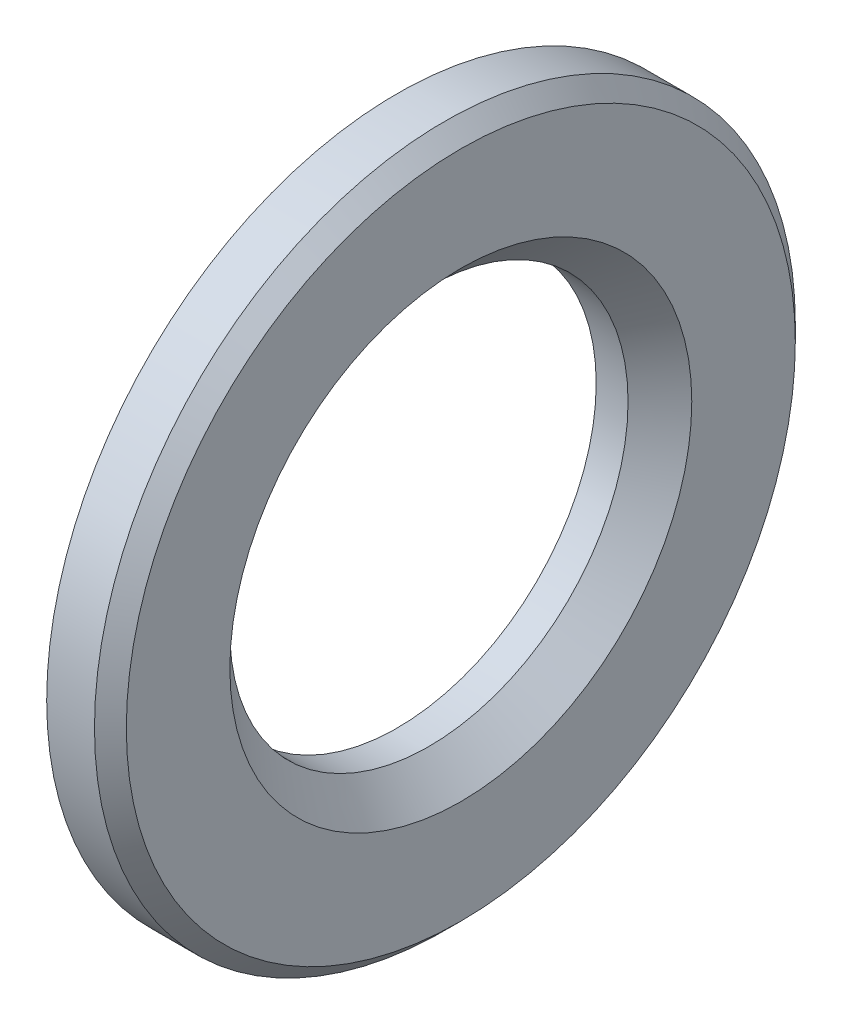
SolidWorks part; units mm, degrees
ref_plane "Plane1" through (0, 0, 0) normal (0, 0, 1) x (1, 0, 0)
ref_plane "Plane2" through (0, 0, 0) normal (0, 1, 0) x (1, 0, 0)
ref_plane "Plane3" through (0, 0, 0) normal (1, 0, 0) x (0, 0, -1)
sketch "Sketch1" plane through (0, 0, 0) normal (1, 0, 0) x (0, 0, -1)
  circle A0 centre (0, 0) radius 12.5
  circle A1 centre (0, 0) radius 22
  dimension "InsideDia" = 25
  dimension "OutsideDia" = 44
extrude "Base-Extrude" add sketch "Sketch1" along normal blind 4
chamfer "IDchamfer" distance 2 angle 45 1 edges at (4, 0, -12.5)
chamfer "ODchamfer" distance 1 angle 45 1 edges at (4, 0, -22)
